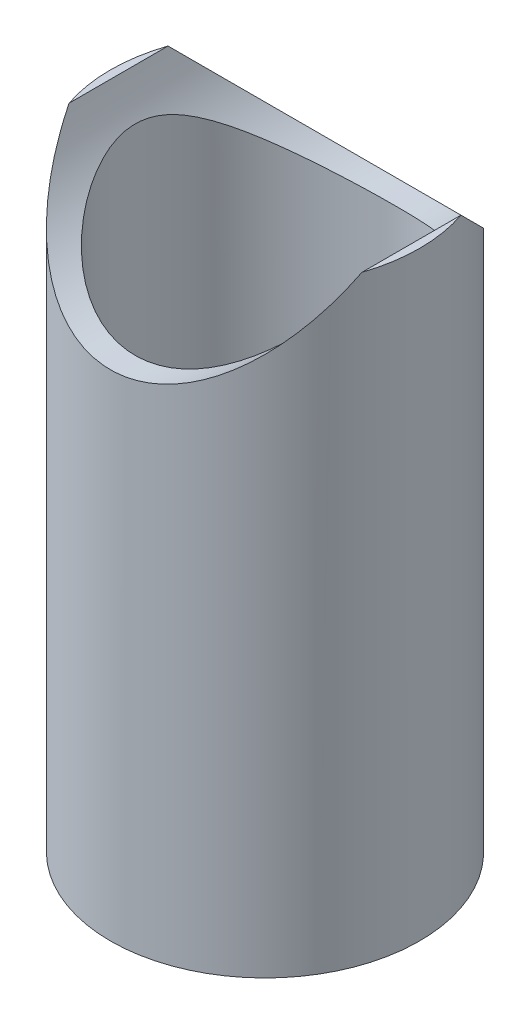
SolidWorks part; units mm, degrees
ref_plane "Спереди" through (0, 0, 0) normal (0, 0, 1) x (1, 0, 0)
ref_plane "Сверху" through (0, 0, 0) normal (0, 1, 0) x (1, 0, 0)
ref_plane "Справа" through (0, 0, 0) normal (1, 0, 0) x (0, 0, -1)
sketch "Эскиз1" plane through (0, 0, 0) normal (0, 1, 0) x (1, 0, 0)
  circle A0 centre (0, 0) radius 12.5
  circle A1 centre (0, 0) radius 10.5
  dimension "D1" = 25
  dimension "D2" = 21
extrude "Бобышка-Вытянуть1" add sketch "Эскиз1" along normal blind 48.5
sketch "Эскиз2" plane through (0, 0, 0) normal (0, 0, 1) x (1, 0, 0)
  line L1 (10.5, 48.5) -> (-10.5, 48.5) construction
  circle A0 centre (0, 52.5) radius 12.5
  dimension "D1" = 4
extrude "Вырез-Вытянуть1" cut sketch "Эскиз2" against normal through all and the other way through all
sketch "Эскиз3" plane through (0, 0, 0) normal (0, 0, 1) x (1, 0, 0)
  circle A0 centre (0, 15) radius 4
  dimension "D1" = 15
  dimension "D2" = 8
extrude "Вырез-Вытянуть2" cut sketch "Эскиз3" against normal through all
